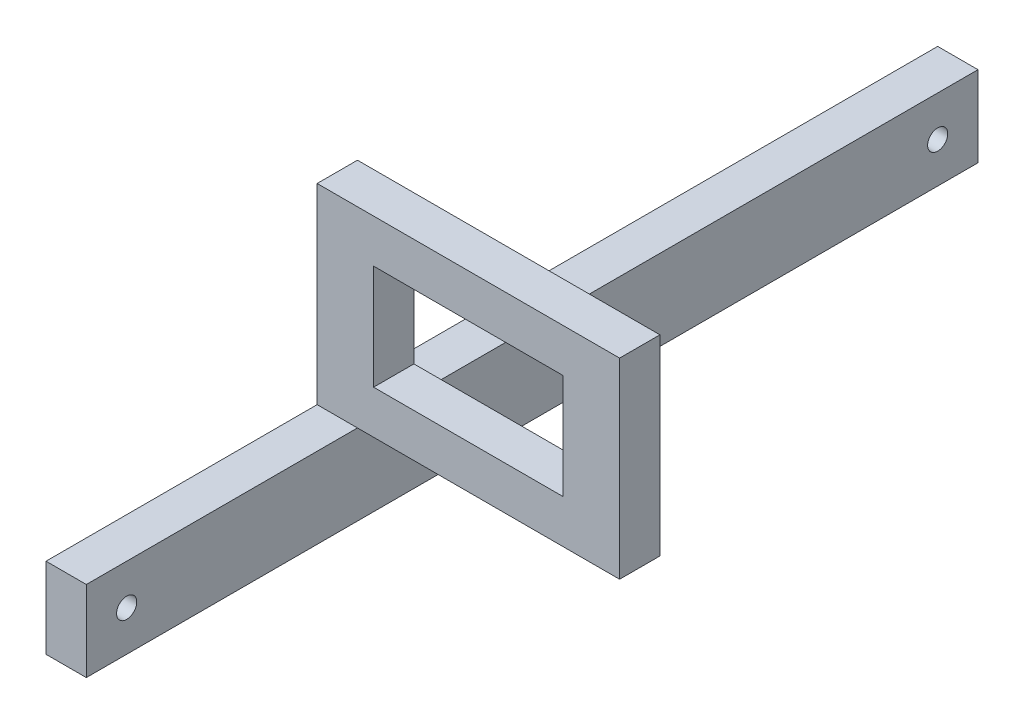
SolidWorks part; units mm, degrees
ref_plane "Front Plane" through (0, 0, 0) normal (0, 0, 1) x (1, 0, 0)
ref_plane "Top Plane" through (0, 0, 0) normal (0, 1, 0) x (1, 0, 0)
ref_plane "Right Plane" through (0, 0, 0) normal (1, 0, 0) x (0, 0, -1)
sketch "Sketch2" plane through (0, 0, 0) normal (0, 0, 1) x (1, 0, 0)
  line L1 (19.05, -12.065) -> (-19.05, -12.065)
  line L2 (19.05, -12.065) -> (19.05, 12.065)
  line L3 (19.05, 12.065) -> (-19.05, 12.065)
  line L4 (-19.05, -12.065) -> (-19.05, 12.065)
  line L5 (19.05, -12.065) -> (-19.05, 12.065) construction
  line L6 (19.05, 12.065) -> (-19.05, -12.065) construction
  point P0 (0, 0)
  dimension "D1" = 38.1
  dimension "D2" = 24.13
extrude "Boss-Extrude1" add sketch "Sketch2" along normal blind 5.08 contours L3 L4 L1 L2
sketch "Sketch3" plane through (0, 0, 5.08) normal (0, 0, 1) x (1, 0, 0)
  line L1 (-11.938, -6.604) -> (11.938, -6.604)
  line L2 (-11.938, -6.604) -> (-11.938, 6.604)
  line L3 (-11.938, 6.604) -> (11.938, 6.604)
  line L4 (11.938, -6.604) -> (11.938, 6.604)
  line L5 (-11.938, -6.604) -> (11.938, 6.604) construction
  line L6 (-11.938, 6.604) -> (11.938, -6.604) construction
  point P0 (0, 0)
  dimension "D1" = 23.876
  dimension ".52" = 13.208
extrude "Cut-Extrude1" cut sketch "Sketch3" against normal blind 5.08
sketch "Sketch4" plane through (0, 0, 5.08) normal (0, 0, 1) x (1, 0, 0)
  line L1 (-19.05, -12.065) -> (-13.97, -12.065)
  line L2 (-19.05, -12.065) -> (-19.05, -22.225)
  line L3 (-19.05, -22.225) -> (-13.97, -22.225)
  line L4 (-13.97, -12.065) -> (-13.97, -22.225)
  line L5 (-19.05, -12.065) -> (-13.97, -22.225) construction
  line L6 (-19.05, -22.225) -> (-13.97, -12.065) construction
  line L8 (-19.05, -12.065) -> (-19.05, 12.065) construction
  line L9 (19.05, -12.065) -> (-19.05, -12.065) construction
  point P0 (-16.51, -17.145)
  dimension "D1" = 5.08
  dimension "D2" = 10.16
extrude "Boss-Extrude2" add sketch "Sketch4" along normal up to surface and the other way up to surface
sketch "Sketch5" plane through (-19.05, 0, 0) normal (-1, 0, 0) x (0, 0, 1)
  line L1 (0, -12.065) -> (-73.0877, -12.065) construction
  line L2 (-73.0877, -22.225) -> (-73.0877, -12.065) construction
  line L3 (39.2348, -22.225) -> (39.2348, -12.065) construction
  line L4 (39.2348, -12.065) -> (5.08, -12.065) construction
  circle A0 centre (-68.0077, -17.145) radius 1.27
  circle A1 centre (34.1548, -17.145) radius 1.27
  dimension "D1" = 2.54
  dimension "D2" = 2.54
  dimension "D3" = 5.08
  dimension "D4" = 5.08
  dimension "D5" = 5.08
  dimension "D6" = 5.08
extrude "Cut-Extrude2" cut sketch "Sketch5" against normal up to surface (5.08 mm away)
